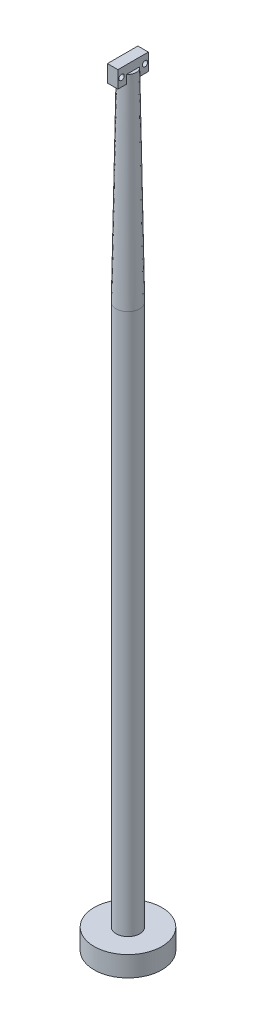
SolidWorks part; units mm, degrees
ref_plane "Alzado" through (0, 0, 0) normal (0, 0, 1) x (1, 0, 0)
ref_plane "Planta" through (0, 0, 0) normal (0, 1, 0) x (1, 0, 0)
ref_plane "Vista lateral" through (0, 0, 0) normal (1, 0, 0) x (0, 0, -1)
sketch "Croquis1" plane through (0, 0, 0) normal (0, 1, 0) x (1, 0, 0)
  circle A0 centre (0, 0) radius 500
  dimension "D1" = 1000
extrude "Saliente-Extruir1" add sketch "Croquis1" along normal blind 300
sketch "Croquis2" plane through (0, 300, 0) normal (0, 1, 0) x (1, 0, 0)
  circle A0 centre (0, 0) radius 175
  dimension "D1" = 350
extrude "Saliente-Extruir3" add sketch "Croquis2" along normal blind 8000 contours A0
sketch "Croquis4" plane through (0, 8300, 0) normal (0, 1, 0) x (1, 0, 0)
  circle A0 centre (0, 0) radius 175
extrude "Saliente-Extruir5" add sketch "Croquis4" along normal blind 3000 draft 1
ref_plane "Plano1" through (0, 0, 0) normal (0, 0, 1) x (1, 0, 0)
sketch "Croquis5" plane through (0, 11300, 0) normal (0, 1, 0) x (1, 0, 0)
  line L0 (0, 0) -> (0, -122.6348)
  circle A0 centre (0, 0) radius 122.6348 construction
ref_plane "Plano2" through (0, 0, 0) normal (-1, 0, 0) x (0, 0, 1)
sketch "Croquis6" plane through (0, 0, 0) normal (-1, 0, 0) x (0, 0, 1)
  line L0 (122.6348, 11300) -> (-122.6348, 11300) construction
  line L1 (225, 11425) -> (-225, 11425)
  line L2 (225, 11425) -> (225, 11175)
  line L3 (225, 11175) -> (-225, 11175)
  line L4 (-225, 11425) -> (-225, 11175)
  line L5 (225, 11425) -> (-225, 11175) construction
  line L6 (225, 11175) -> (-225, 11425) construction
  circle A0 centre (-176.0053, 11300) radius 40
  circle A1 centre (171.3729, 11300) radius 40
  point P0 (0, 11300)
  dimension "D1" = 80
  dimension "D2" = 80
  dimension "D3" = 250
  dimension "D4" = 450
extrude "Saliente-Extruir6" add sketch "Croquis6" along normal blind 79 and the other way blind 76
